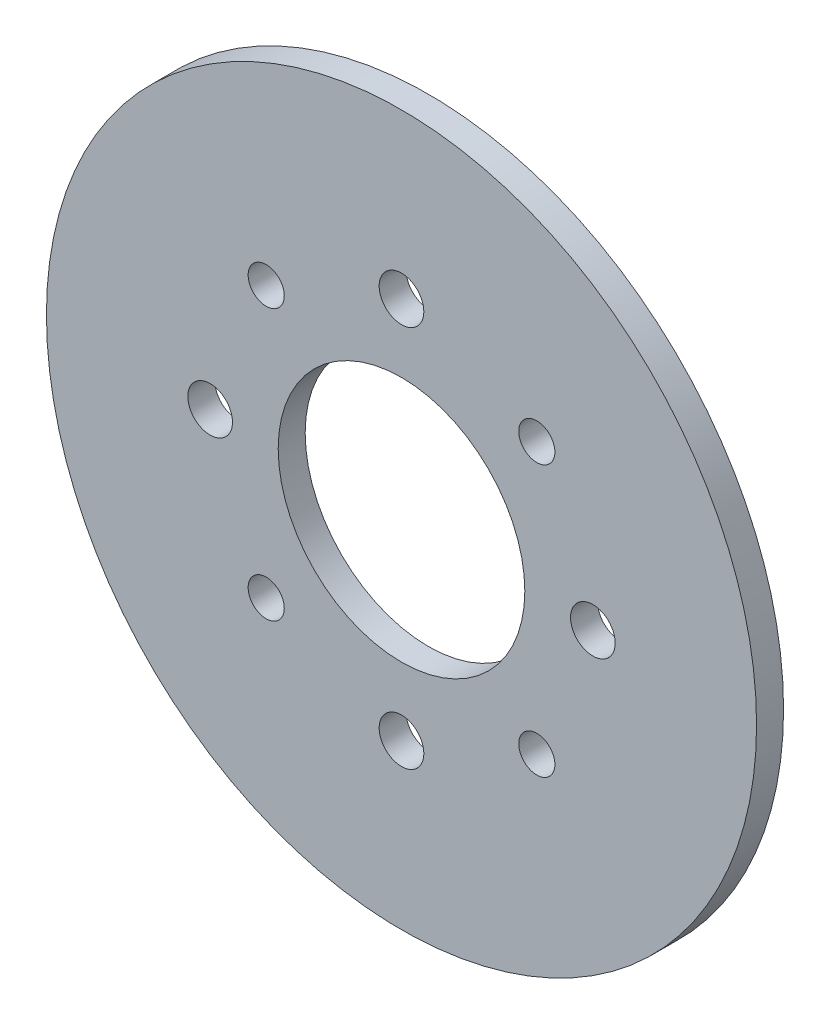
SolidWorks part; units mm, degrees
ref_plane "Front Plane" through (0, 0, 0) normal (0, 0, 1) x (1, 0, 0)
ref_plane "Top Plane" through (0, 0, 0) normal (0, 1, 0) x (1, 0, 0)
ref_plane "Right Plane" through (0, 0, 0) normal (1, 0, 0) x (0, 0, -1)
sketch "Sketch1" plane through (0, 0, 0) normal (0, 0, 1) x (1, 0, 0)
  circle A3 centre (0, 45) radius 5.25
  circle A4 centre (45, 0) radius 5.25
  circle A5 centre (0, -45) radius 5.25
  circle A6 centre (-45, 0) radius 5.25
  circle A7 centre (31.8198, 31.8198) radius 4.25
  circle A8 centre (31.8198, -31.8198) radius 4.25
  circle A9 centre (-31.8198, -31.8198) radius 4.25
  circle A10 centre (-31.8198, 31.8198) radius 4.25
  circle A11 centre (0, 0) radius 29
  circle A12 centre (0, 0) radius 83.5034
  point P14 (0, 0)
  point P22 (0, 0)
  dimension "D1" = 45
  dimension "D2" = 10.5
  dimension "D4" = 8.5
  dimension "D8" = 58
  dimension "D9" = 167.0067
  dimension "D5" = 45
  dimension "D7" = 31.8198
  dimension "D3" = 4
  dimension "D6" = 4
extrude "Boss-Extrude1" add sketch "Sketch1" along normal blind 6.35
ref_plane "Diff Sprocket Middle Plane" through (0, 0, 3.175) normal (0, 0, -1) x (-1, 0, 0)
